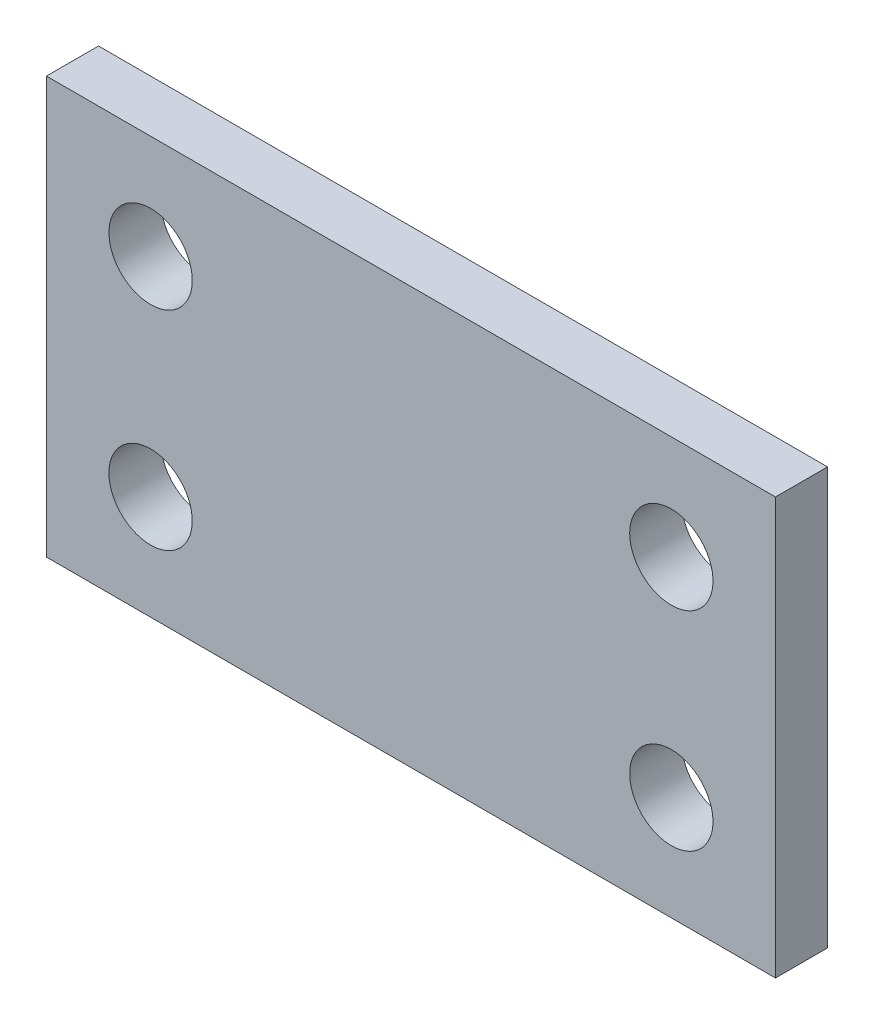
SolidWorks part; units mm, degrees
ref_plane "Płaszczyzna przednia" through (0, 0, 0) normal (0, 0, 1) x (1, 0, 0)
ref_plane "Płaszczyzna górna" through (0, 0, 0) normal (0, 1, 0) x (1, 0, 0)
ref_plane "Płaszczyzna prawa" through (0, 0, 0) normal (1, 0, 0) x (0, 0, -1)
sketch "Szkic1" plane through (0, 0, 0) normal (0, 0, 1) x (1, 0, 0)
  line L0 (0, -55) -> (0, 55) construction
  line L1 (-70, 40) -> (70, 40)
  line L2 (-70, 40) -> (-70, -40)
  line L3 (-70, -40) -> (70, -40)
  line L4 (70, 40) -> (70, -40)
  line L7 (55, 0) -> (-55, 0) construction
  circle A0 centre (-50, 20) radius 8
  circle A2 centre (50, 20) radius 8
  circle A3 centre (50, -20) radius 8
  circle A4 centre (-50, -20) radius 8
  point P0 (0, 0)
  point P8 (-70, 0)
  point P9 (0, -40)
  dimension "D3" = 16
  dimension "D5" = 80
  dimension "D1" = 20
  dimension "D2" = 20
  dimension "D4" = 140
extrude "Dodanie-wyciągnięcie1" add sketch "Szkic1" along normal blind 10
